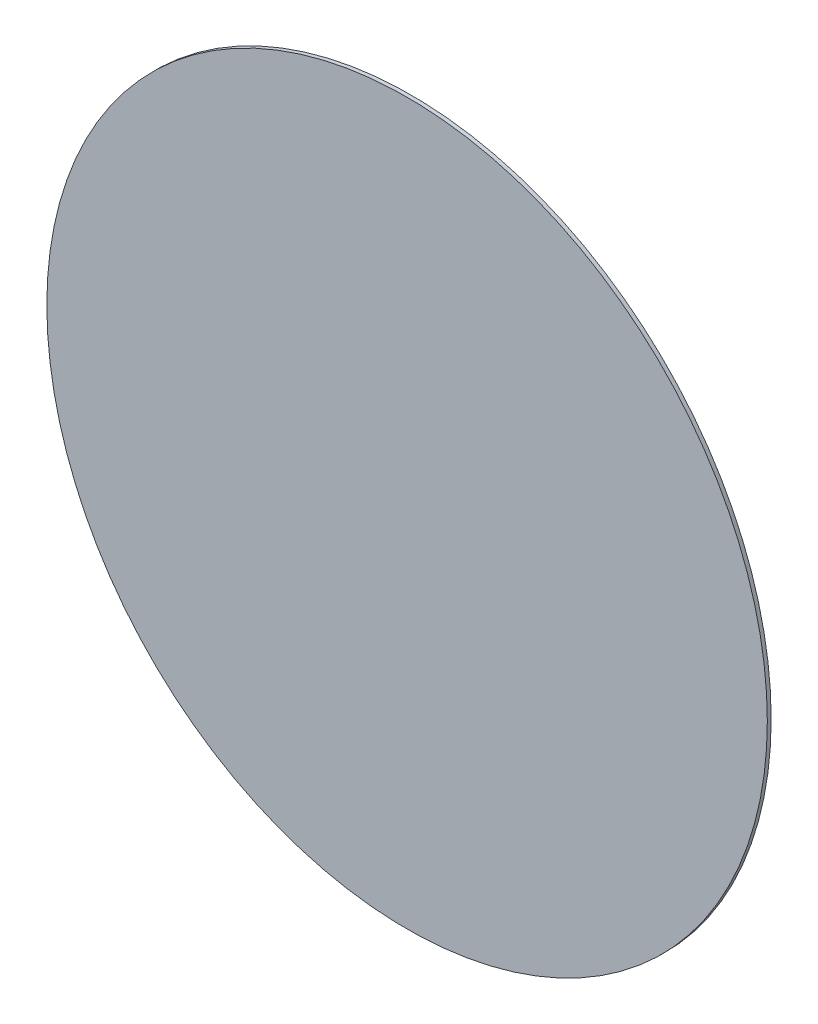
SolidWorks part; units mm, degrees
ref_plane "前视基准面" through (0, 0, 0) normal (0, 0, 1) x (1, 0, 0)
ref_plane "上视基准面" through (0, 0, 0) normal (0, 1, 0) x (1, 0, 0)
ref_plane "右视基准面" through (0, 0, 0) normal (1, 0, 0) x (0, 0, -1)
other "Configuration Table"
sketch "PCB_Outline_Pilot" plane through (0, 0, 0) normal (0, 0, 1) x (1, 0, 0)
  circle A0 centre (0, 0) radius 150
extrude "PCB_1p6mm_Pilot" add sketch "PCB_Outline_Pilot" along normal blind 1.6
